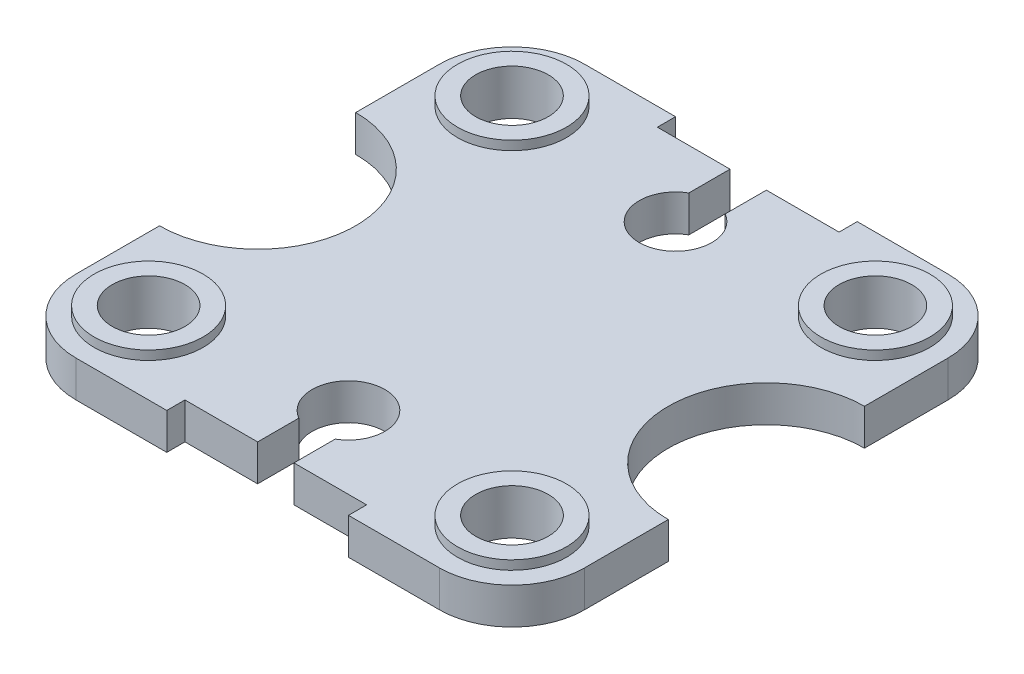
SolidWorks part; units mm, degrees
ref_plane "Front Plane" through (0, 0, 0) normal (0, 0, 1) x (1, 0, 0)
ref_plane "Top Plane" through (0, 0, 0) normal (0, 1, 0) x (1, 0, 0)
ref_plane "Right Plane" through (0, 0, 0) normal (1, 0, 0) x (0, 0, -1)
sketch "Sketch1" plane through (0, 0, 0) normal (0, 1, 0) x (1, 0, 0)
  line L0 (0, -1280) -> (0, -140) construction
  line L1 (-100, 140) -> (-50, 140)
  line L2 (-140, 100) -> (-140, 54)
  line L3 (-100, -140) -> (-50, -140)
  line L5 (-140, 140) -> (0, 0) construction
  line L6 (-140, -140) -> (0, 0) construction
  line L7 (0, 0) -> (50000, 0) construction
  line L8 (-140, -54) -> (-140, -100)
  line L9 (50, 140) -> (100, 140)
  line L10 (-50, -140) -> (-50, -130)
  line L11 (-50, -130) -> (-10, -130)
  line L12 (-10, -130) -> (-10, -107.3205)
  line L13 (-50, 140) -> (-50, 130)
  line L14 (-10, 130) -> (-10, 107.3205)
  line L15 (-50, 130) -> (-10, 130)
  line L16 (50, 130) -> (10, 130)
  line L17 (10, 130) -> (10, 107.3205)
  line L18 (50, 140) -> (50, 130)
  line L19 (10, -130) -> (10, -107.3205)
  line L20 (50, -130) -> (10, -130)
  line L21 (50, -140) -> (50, -130)
  line L22 (140, -54) -> (140, -100)
  line L23 (140, 100) -> (140, 54)
  line L24 (50, -140) -> (100, -140)
  line L25 (0, -70) -> (0, 70) construction
  arc A0 (-140, -54) -> (-140, 54) centre (-140, 0) ccw
  circle A1 centre (-100, -100) radius 20
  circle A2 centre (-100, 100) radius 20
  arc A3 (-140, -100) -> (-100, -140) centre (-100, -100) ccw
  arc A4 (-100, 140) -> (-140, 100) centre (-100, 100) ccw
  arc A5 (10, -107.3205) -> (-10, -107.3205) centre (0, -90) ccw
  arc A6 (10, 107.3205) -> (-10, 107.3205) centre (0, 90) cw
  arc A7 (100, 140) -> (140, 100) centre (100, 100) cw
  arc A8 (140, -100) -> (100, -140) centre (100, -100) cw
  circle A9 centre (100, 100) radius 20
  circle A10 centre (100, -100) radius 20
  arc A11 (140, -54) -> (140, 54) centre (140, 0) cw
  point P0 (0, 0)
  point P13 (0, 0)
  dimension "D3" = 108
  dimension "D7" = 40
  dimension "D8" = 40
  dimension "D1" = 40
  dimension "D11" = 40
  dimension "D2" = 50
  dimension "D4" = 100
  dimension "D5" = 100
  dimension "D6" = 100
  dimension "D9" = 10
  dimension "D10" = 40
  dimension "D12" = 50
  dimension "D13" = 280
  dimension "D14" = 280
  dimension "D15" = 20
  dimension "D16" = 10
extrude "Boss-Extrude1" add sketch "Sketch1" along normal blind 20
sketch "Sketch2" plane through (0, 20, 0) normal (0, 1, 0) x (1, 0, 0)
  line L0 (0, 0) -> (0, 50000) construction
  line L1 (0, 0) -> (50000, 0) construction
  circle A0 centre (-100, 100) radius 30
  circle A1 centre (-100, 100) radius 20
  circle A2 centre (100, 100) radius 30
  circle A3 centre (100, 100) radius 20
  circle A4 centre (100, -100) radius 20
  circle A5 centre (100, -100) radius 30
  circle A6 centre (-100, -100) radius 20
  circle A7 centre (-100, -100) radius 30
  dimension "D1" = 40
  dimension "D2" = 60
extrude "Boss-Extrude2" add sketch "Sketch2" along normal blind 5
